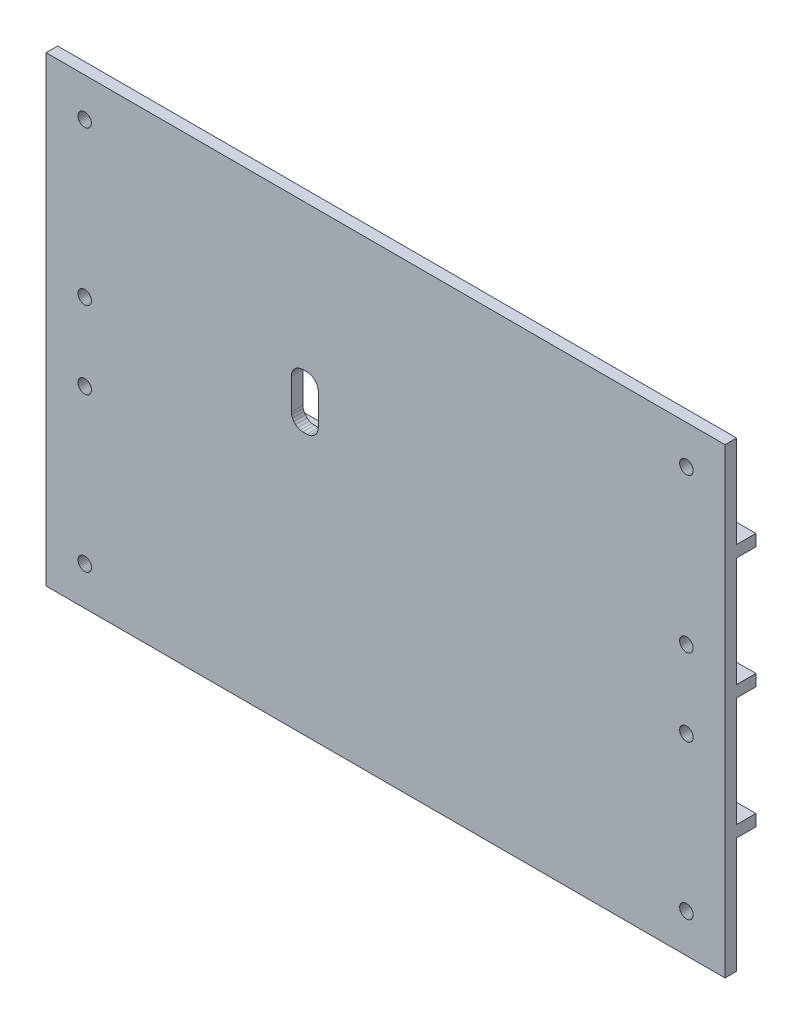
SolidWorks part; units mm, degrees
ref_plane "前视基准面" through (0, 0, 0) normal (0, 0, 1) x (1, 0, 0)
ref_plane "上视基准面" through (0, 0, 0) normal (0, 1, 0) x (1, 0, 0)
ref_plane "右视基准面" through (0, 0, 0) normal (1, 0, 0) x (0, 0, -1)
other "Configuration Table"
ref_plane "基准面1" through (0, 0, -5) normal (0, 0, -1) x (-1, 0, 0)
sketch "草图1" plane through (0, 0, -5) normal (0, 0, -1) x (-1, 0, 0)
  line L0 (-175.8, 0) -> (-175.8, -119.6)
  line L1 (-175.8, -119.6) -> (0, -119.6)
  line L2 (0, -119.6) -> (0, 0)
  line L3 (0, 0) -> (-175.8, 0)
extrude "凸台-拉伸1" add sketch "草图1" against normal blind 8
sketch "草图2" plane through (175.8, 0, 0) normal (1, 0, 0) x (0, 0, -1)
  line L0 (5, -119.6) -> (5, -89.7)
  line L1 (5, -89.7) -> (0, -89.7)
  line L2 (0, -89.7) -> (0, -119.6)
  line L3 (0, -119.6) -> (5, -119.6)
extrude "切除-拉伸1" cut sketch "草图2" against normal through all
sketch "草图3" plane through (175.8, 0, 0) normal (1, 0, 0) x (0, 0, -1)
  line L0 (0, 0) -> (0, -23.9)
  line L1 (0, -23.9) -> (5, -23.9)
  line L2 (5, -23.9) -> (5, 0)
  line L3 (5, 0) -> (0, 0)
extrude "切除-拉伸2" cut sketch "草图3" against normal through all
sketch "草图4" plane through (175.8, 0, 0) normal (1, 0, 0) x (0, 0, -1)
  line L0 (5, -55.3) -> (5, -26.9)
  line L1 (5, -26.9) -> (0, -26.9)
  line L2 (0, -26.9) -> (0, -55.3)
  line L3 (0, -55.3) -> (5, -55.3)
extrude "切除-拉伸3" cut sketch "草图4" against normal through all
sketch "草图5" plane through (175.8, 0, 0) normal (1, 0, 0) x (0, 0, -1)
  line L0 (5, -86.7) -> (5, -58.3)
  line L1 (5, -58.3) -> (0, -58.3)
  line L2 (0, -58.3) -> (0, -86.7)
  line L3 (0, -86.7) -> (5, -86.7)
extrude "切除-拉伸4" cut sketch "草图5" against normal through all
sketch "草图6" plane through (0, 0, 0) normal (0, 0, -1) x (-1, 0, 0)
  line L0 (-9.7257, -48.0716) -> (-10, -48.0506)
  line L1 (-10, -48.0506) -> (-10.2743, -48.0716)
  line L2 (-10.2743, -48.0716) -> (-10.54, -48.136)
  line L3 (-10.54, -48.136) -> (-10.7954, -48.2414)
  line L4 (-10.7954, -48.2414) -> (-11.0275, -48.3839)
  line L5 (-11.0275, -48.3839) -> (-11.238, -48.5636)
  line L6 (-11.238, -48.5636) -> (-11.4149, -48.7706)
  line L7 (-11.4149, -48.7706) -> (-11.5592, -49.0065)
  line L8 (-11.5592, -49.0065) -> (-11.6639, -49.2581)
  line L9 (-11.6639, -49.2581) -> (-11.7271, -49.5217)
  line L10 (-11.7271, -49.5217) -> (-11.75, -49.8)
  line L11 (-11.75, -49.8) -> (-11.7271, -50.0783)
  line L12 (-11.7271, -50.0783) -> (-11.6639, -50.3419)
  line L13 (-11.6639, -50.3419) -> (-11.5592, -50.5935)
  line L14 (-11.5592, -50.5935) -> (-11.4149, -50.8294)
  line L15 (-11.4149, -50.8294) -> (-11.238, -51.0364)
  line L16 (-11.238, -51.0364) -> (-11.0275, -51.2161)
  line L17 (-11.0275, -51.2161) -> (-10.7954, -51.3586)
  line L18 (-10.7954, -51.3586) -> (-10.54, -51.464)
  line L19 (-10.54, -51.464) -> (-10.2743, -51.5283)
  line L20 (-10.2743, -51.5283) -> (-10, -51.5494)
  line L21 (-10, -51.5494) -> (-9.7257, -51.5283)
  line L22 (-9.7257, -51.5283) -> (-9.46, -51.464)
  line L23 (-9.46, -51.464) -> (-9.2046, -51.3586)
  line L24 (-9.2046, -51.3586) -> (-8.9725, -51.2161)
  line L25 (-8.9725, -51.2161) -> (-8.762, -51.0364)
  line L26 (-8.762, -51.0364) -> (-8.5851, -50.8294)
  line L27 (-8.5851, -50.8294) -> (-8.4408, -50.5935)
  line L28 (-8.4408, -50.5935) -> (-8.3361, -50.3419)
  line L29 (-8.3361, -50.3419) -> (-8.2729, -50.0783)
  line L30 (-8.2729, -50.0783) -> (-8.25, -49.8)
  line L31 (-8.25, -49.8) -> (-8.2729, -49.5217)
  line L32 (-8.2729, -49.5217) -> (-8.3361, -49.2581)
  line L33 (-8.3361, -49.2581) -> (-8.4408, -49.0065)
  line L34 (-8.4408, -49.0065) -> (-8.5851, -48.7706)
  line L35 (-8.5851, -48.7706) -> (-8.762, -48.5636)
  line L36 (-8.762, -48.5636) -> (-8.9725, -48.3839)
  line L37 (-8.9725, -48.3839) -> (-9.2046, -48.2414)
  line L38 (-9.2046, -48.2414) -> (-9.46, -48.136)
  line L39 (-9.46, -48.136) -> (-9.7257, -48.0716)
extrude "切除-拉伸5" cut sketch "草图6" against normal through all
sketch "草图7" plane through (0, 0, 0) normal (0, 0, -1) x (-1, 0, 0)
  line L0 (-67.5, -37.8) -> (-68.1688, -37.8755)
  line L1 (-68.1688, -37.8755) -> (-68.8023, -38.0976)
  line L2 (-68.8023, -38.0976) -> (-69.3705, -38.4549)
  line L3 (-69.3705, -38.4549) -> (-69.8451, -38.9295)
  line L4 (-69.8451, -38.9295) -> (-70.2024, -39.4977)
  line L5 (-70.2024, -39.4977) -> (-70.4245, -40.1312)
  line L6 (-70.4245, -40.1312) -> (-70.5, -40.8)
  line L7 (-70.5, -40.8) -> (-70.5, -48.8)
  line L8 (-70.5, -48.8) -> (-70.4245, -49.4688)
  line L9 (-70.4245, -49.4688) -> (-70.2024, -50.1023)
  line L10 (-70.2024, -50.1023) -> (-69.8451, -50.6705)
  line L11 (-69.8451, -50.6705) -> (-69.3705, -51.1451)
  line L12 (-69.3705, -51.1451) -> (-68.8023, -51.5024)
  line L13 (-68.8023, -51.5024) -> (-68.1688, -51.7245)
  line L14 (-68.1688, -51.7245) -> (-67.5, -51.8)
  line L15 (-67.5, -51.8) -> (-66.5, -51.8)
  line L16 (-66.5, -51.8) -> (-65.8312, -51.7245)
  line L17 (-65.8312, -51.7245) -> (-65.1977, -51.5024)
  line L18 (-65.1977, -51.5024) -> (-64.6295, -51.1451)
  line L19 (-64.6295, -51.1451) -> (-64.1549, -50.6705)
  line L20 (-64.1549, -50.6705) -> (-63.7976, -50.1023)
  line L21 (-63.7976, -50.1023) -> (-63.5755, -49.4688)
  line L22 (-63.5755, -49.4688) -> (-63.5, -48.8)
  line L23 (-63.5, -48.8) -> (-63.5, -40.8)
  line L24 (-63.5, -40.8) -> (-63.5755, -40.1312)
  line L25 (-63.5755, -40.1312) -> (-63.7976, -39.4977)
  line L26 (-63.7976, -39.4977) -> (-64.1549, -38.9295)
  line L27 (-64.1549, -38.9295) -> (-64.6295, -38.4549)
  line L28 (-64.6295, -38.4549) -> (-65.1977, -38.0976)
  line L29 (-65.1977, -38.0976) -> (-65.8312, -37.8755)
  line L30 (-65.8312, -37.8755) -> (-66.5, -37.8)
  line L31 (-66.5, -37.8) -> (-67.5, -37.8)
extrude "切除-拉伸6" cut sketch "草图7" against normal through all
sketch "草图8" plane through (0, 0, 3) normal (0, 0, 1) x (1, 0, 0)
  line L0 (167.4639, -49.2581) -> (167.3592, -49.0065)
  line L1 (167.3592, -49.0065) -> (167.2149, -48.7706)
  line L2 (167.2149, -48.7706) -> (167.038, -48.5636)
  line L3 (167.038, -48.5636) -> (166.8275, -48.3839)
  line L4 (166.8275, -48.3839) -> (166.5954, -48.2414)
  line L5 (166.5954, -48.2414) -> (166.34, -48.136)
  line L6 (166.34, -48.136) -> (166.0743, -48.0716)
  line L7 (166.0743, -48.0716) -> (165.8, -48.0506)
  line L8 (165.8, -48.0506) -> (165.5257, -48.0716)
  line L9 (165.5257, -48.0716) -> (165.26, -48.136)
  line L10 (165.26, -48.136) -> (165.0046, -48.2414)
  line L11 (165.0046, -48.2414) -> (164.7725, -48.3839)
  line L12 (164.7725, -48.3839) -> (164.562, -48.5636)
  line L13 (164.562, -48.5636) -> (164.3851, -48.7706)
  line L14 (164.3851, -48.7706) -> (164.2408, -49.0065)
  line L15 (164.2408, -49.0065) -> (164.1361, -49.2581)
  line L16 (164.1361, -49.2581) -> (164.0729, -49.5217)
  line L17 (164.0729, -49.5217) -> (164.05, -49.8)
  line L18 (164.05, -49.8) -> (164.0729, -50.0783)
  line L19 (164.0729, -50.0783) -> (164.1361, -50.3419)
  line L20 (164.1361, -50.3419) -> (164.2408, -50.5935)
  line L21 (164.2408, -50.5935) -> (164.3851, -50.8294)
  line L22 (164.3851, -50.8294) -> (164.562, -51.0364)
  line L23 (164.562, -51.0364) -> (164.7725, -51.2161)
  line L24 (164.7725, -51.2161) -> (165.0046, -51.3586)
  line L25 (165.0046, -51.3586) -> (165.26, -51.464)
  line L26 (165.26, -51.464) -> (165.5257, -51.5283)
  line L27 (165.5257, -51.5283) -> (165.8, -51.5494)
  line L28 (165.8, -51.5494) -> (166.0743, -51.5283)
  line L29 (166.0743, -51.5283) -> (166.34, -51.464)
  line L30 (166.34, -51.464) -> (166.5954, -51.3586)
  line L31 (166.5954, -51.3586) -> (166.8275, -51.2161)
  line L32 (166.8275, -51.2161) -> (167.038, -51.0364)
  line L33 (167.038, -51.0364) -> (167.2149, -50.8294)
  line L34 (167.2149, -50.8294) -> (167.3592, -50.5935)
  line L35 (167.3592, -50.5935) -> (167.4639, -50.3419)
  line L36 (167.4639, -50.3419) -> (167.527, -50.0783)
  line L37 (167.527, -50.0783) -> (167.55, -49.8)
  line L38 (167.55, -49.8) -> (167.527, -49.5217)
  line L39 (167.527, -49.5217) -> (167.4639, -49.2581)
extrude "切除-拉伸7" cut sketch "草图8" against normal through all
sketch "草图9" plane through (0, 0, 0) normal (0, 0, -1) x (-1, 0, 0)
  line L0 (-8.25, -10) -> (-8.2729, -9.7217)
  line L1 (-8.2729, -9.7217) -> (-8.3361, -9.4581)
  line L2 (-8.3361, -9.4581) -> (-8.4408, -9.2065)
  line L3 (-8.4408, -9.2065) -> (-8.5851, -8.9706)
  line L4 (-8.5851, -8.9706) -> (-8.762, -8.7636)
  line L5 (-8.762, -8.7636) -> (-8.9725, -8.5839)
  line L6 (-8.9725, -8.5839) -> (-9.2046, -8.4414)
  line L7 (-9.2046, -8.4414) -> (-9.46, -8.336)
  line L8 (-9.46, -8.336) -> (-9.7257, -8.2716)
  line L9 (-9.7257, -8.2716) -> (-10, -8.2506)
  line L10 (-10, -8.2506) -> (-10.2743, -8.2716)
  line L11 (-10.2743, -8.2716) -> (-10.54, -8.336)
  line L12 (-10.54, -8.336) -> (-10.7954, -8.4414)
  line L13 (-10.7954, -8.4414) -> (-11.0275, -8.5839)
  line L14 (-11.0275, -8.5839) -> (-11.238, -8.7636)
  line L15 (-11.238, -8.7636) -> (-11.4149, -8.9706)
  line L16 (-11.4149, -8.9706) -> (-11.5592, -9.2065)
  line L17 (-11.5592, -9.2065) -> (-11.6639, -9.4581)
  line L18 (-11.6639, -9.4581) -> (-11.7271, -9.7217)
  line L19 (-11.7271, -9.7217) -> (-11.75, -10)
  line L20 (-11.75, -10) -> (-11.7271, -10.2783)
  line L21 (-11.7271, -10.2783) -> (-11.6639, -10.5419)
  line L22 (-11.6639, -10.5419) -> (-11.5592, -10.7935)
  line L23 (-11.5592, -10.7935) -> (-11.4149, -11.0294)
  line L24 (-11.4149, -11.0294) -> (-11.238, -11.2364)
  line L25 (-11.238, -11.2364) -> (-11.0275, -11.4161)
  line L26 (-11.0275, -11.4161) -> (-10.7954, -11.5586)
  line L27 (-10.7954, -11.5586) -> (-10.54, -11.664)
  line L28 (-10.54, -11.664) -> (-10.2743, -11.7284)
  line L29 (-10.2743, -11.7284) -> (-10, -11.7494)
  line L30 (-10, -11.7494) -> (-9.7257, -11.7284)
  line L31 (-9.7257, -11.7284) -> (-9.46, -11.664)
  line L32 (-9.46, -11.664) -> (-9.2046, -11.5586)
  line L33 (-9.2046, -11.5586) -> (-8.9725, -11.4161)
  line L34 (-8.9725, -11.4161) -> (-8.762, -11.2364)
  line L35 (-8.762, -11.2364) -> (-8.5851, -11.0294)
  line L36 (-8.5851, -11.0294) -> (-8.4408, -10.7935)
  line L37 (-8.4408, -10.7935) -> (-8.3361, -10.5419)
  line L38 (-8.3361, -10.5419) -> (-8.2729, -10.2783)
  line L39 (-8.2729, -10.2783) -> (-8.25, -10)
extrude "切除-拉伸8" cut sketch "草图9" against normal through all
sketch "草图10" plane through (0, 0, 3) normal (0, 0, 1) x (1, 0, 0)
  line L0 (166.0743, -8.2716) -> (165.8, -8.2506)
  line L1 (165.8, -8.2506) -> (165.5257, -8.2716)
  line L2 (165.5257, -8.2716) -> (165.26, -8.336)
  line L3 (165.26, -8.336) -> (165.0046, -8.4414)
  line L4 (165.0046, -8.4414) -> (164.7725, -8.5839)
  line L5 (164.7725, -8.5839) -> (164.562, -8.7636)
  line L6 (164.562, -8.7636) -> (164.3851, -8.9706)
  line L7 (164.3851, -8.9706) -> (164.2408, -9.2065)
  line L8 (164.2408, -9.2065) -> (164.1361, -9.4581)
  line L9 (164.1361, -9.4581) -> (164.0729, -9.7217)
  line L10 (164.0729, -9.7217) -> (164.05, -10)
  line L11 (164.05, -10) -> (164.0729, -10.2783)
  line L12 (164.0729, -10.2783) -> (164.1361, -10.5419)
  line L13 (164.1361, -10.5419) -> (164.2408, -10.7935)
  line L14 (164.2408, -10.7935) -> (164.3851, -11.0294)
  line L15 (164.3851, -11.0294) -> (164.562, -11.2364)
  line L16 (164.562, -11.2364) -> (164.7725, -11.4161)
  line L17 (164.7725, -11.4161) -> (165.0046, -11.5586)
  line L18 (165.0046, -11.5586) -> (165.26, -11.664)
  line L19 (165.26, -11.664) -> (165.5257, -11.7284)
  line L20 (165.5257, -11.7284) -> (165.8, -11.7494)
  line L21 (165.8, -11.7494) -> (166.0743, -11.7284)
  line L22 (166.0743, -11.7284) -> (166.34, -11.664)
  line L23 (166.34, -11.664) -> (166.5954, -11.5586)
  line L24 (166.5954, -11.5586) -> (166.8275, -11.4161)
  line L25 (166.8275, -11.4161) -> (167.038, -11.2364)
  line L26 (167.038, -11.2364) -> (167.2149, -11.0294)
  line L27 (167.2149, -11.0294) -> (167.3592, -10.7935)
  line L28 (167.3592, -10.7935) -> (167.4639, -10.5419)
  line L29 (167.4639, -10.5419) -> (167.527, -10.2783)
  line L30 (167.527, -10.2783) -> (167.55, -10)
  line L31 (167.55, -10) -> (167.527, -9.7217)
  line L32 (167.527, -9.7217) -> (167.4639, -9.4581)
  line L33 (167.4639, -9.4581) -> (167.3592, -9.2065)
  line L34 (167.3592, -9.2065) -> (167.2149, -8.9706)
  line L35 (167.2149, -8.9706) -> (167.038, -8.7636)
  line L36 (167.038, -8.7636) -> (166.8275, -8.5839)
  line L37 (166.8275, -8.5839) -> (166.5954, -8.4414)
  line L38 (166.5954, -8.4414) -> (166.34, -8.336)
  line L39 (166.34, -8.336) -> (166.0743, -8.2716)
extrude "切除-拉伸9" cut sketch "草图10" against normal through all
sketch "草图11" plane through (0, 0, 0) normal (0, 0, -1) x (-1, 0, 0)
  line L0 (-11.75, -69.8) -> (-11.7271, -70.0783)
  line L1 (-11.7271, -70.0783) -> (-11.6639, -70.3419)
  line L2 (-11.6639, -70.3419) -> (-11.5592, -70.5935)
  line L3 (-11.5592, -70.5935) -> (-11.4149, -70.8294)
  line L4 (-11.4149, -70.8294) -> (-11.238, -71.0364)
  line L5 (-11.238, -71.0364) -> (-11.0275, -71.2161)
  line L6 (-11.0275, -71.2161) -> (-10.7954, -71.3586)
  line L7 (-10.7954, -71.3586) -> (-10.54, -71.464)
  line L8 (-10.54, -71.464) -> (-10.2743, -71.5284)
  line L9 (-10.2743, -71.5284) -> (-10, -71.5494)
  line L10 (-10, -71.5494) -> (-9.7257, -71.5284)
  line L11 (-9.7257, -71.5284) -> (-9.46, -71.464)
  line L12 (-9.46, -71.464) -> (-9.2046, -71.3586)
  line L13 (-9.2046, -71.3586) -> (-8.9725, -71.2161)
  line L14 (-8.9725, -71.2161) -> (-8.762, -71.0364)
  line L15 (-8.762, -71.0364) -> (-8.5851, -70.8294)
  line L16 (-8.5851, -70.8294) -> (-8.4408, -70.5935)
  line L17 (-8.4408, -70.5935) -> (-8.3361, -70.3419)
  line L18 (-8.3361, -70.3419) -> (-8.2729, -70.0783)
  line L19 (-8.2729, -70.0783) -> (-8.25, -69.8)
  line L20 (-8.25, -69.8) -> (-8.2729, -69.5217)
  line L21 (-8.2729, -69.5217) -> (-8.3361, -69.2581)
  line L22 (-8.3361, -69.2581) -> (-8.4408, -69.0065)
  line L23 (-8.4408, -69.0065) -> (-8.5851, -68.7706)
  line L24 (-8.5851, -68.7706) -> (-8.762, -68.5636)
  line L25 (-8.762, -68.5636) -> (-8.9725, -68.3839)
  line L26 (-8.9725, -68.3839) -> (-9.2046, -68.2414)
  line L27 (-9.2046, -68.2414) -> (-9.46, -68.136)
  line L28 (-9.46, -68.136) -> (-9.7257, -68.0716)
  line L29 (-9.7257, -68.0716) -> (-10, -68.0506)
  line L30 (-10, -68.0506) -> (-10.2743, -68.0716)
  line L31 (-10.2743, -68.0716) -> (-10.54, -68.136)
  line L32 (-10.54, -68.136) -> (-10.7954, -68.2414)
  line L33 (-10.7954, -68.2414) -> (-11.0275, -68.3839)
  line L34 (-11.0275, -68.3839) -> (-11.238, -68.5636)
  line L35 (-11.238, -68.5636) -> (-11.4149, -68.7706)
  line L36 (-11.4149, -68.7706) -> (-11.5592, -69.0065)
  line L37 (-11.5592, -69.0065) -> (-11.6639, -69.2581)
  line L38 (-11.6639, -69.2581) -> (-11.7271, -69.5217)
  line L39 (-11.7271, -69.5217) -> (-11.75, -69.8)
extrude "切除-拉伸10" cut sketch "草图11" against normal through all
sketch "草图12" plane through (0, 0, 3) normal (0, 0, 1) x (1, 0, 0)
  line L0 (164.1361, -69.2581) -> (164.0729, -69.5217)
  line L1 (164.0729, -69.5217) -> (164.05, -69.8)
  line L2 (164.05, -69.8) -> (164.0729, -70.0783)
  line L3 (164.0729, -70.0783) -> (164.1361, -70.3419)
  line L4 (164.1361, -70.3419) -> (164.2408, -70.5935)
  line L5 (164.2408, -70.5935) -> (164.3851, -70.8294)
  line L6 (164.3851, -70.8294) -> (164.562, -71.0364)
  line L7 (164.562, -71.0364) -> (164.7725, -71.2161)
  line L8 (164.7725, -71.2161) -> (165.0046, -71.3586)
  line L9 (165.0046, -71.3586) -> (165.26, -71.464)
  line L10 (165.26, -71.464) -> (165.5257, -71.5284)
  line L11 (165.5257, -71.5284) -> (165.8, -71.5494)
  line L12 (165.8, -71.5494) -> (166.0743, -71.5284)
  line L13 (166.0743, -71.5284) -> (166.34, -71.464)
  line L14 (166.34, -71.464) -> (166.5954, -71.3586)
  line L15 (166.5954, -71.3586) -> (166.8275, -71.2161)
  line L16 (166.8275, -71.2161) -> (167.038, -71.0364)
  line L17 (167.038, -71.0364) -> (167.2149, -70.8294)
  line L18 (167.2149, -70.8294) -> (167.3592, -70.5935)
  line L19 (167.3592, -70.5935) -> (167.4639, -70.3419)
  line L20 (167.4639, -70.3419) -> (167.527, -70.0783)
  line L21 (167.527, -70.0783) -> (167.55, -69.8)
  line L22 (167.55, -69.8) -> (167.527, -69.5217)
  line L23 (167.527, -69.5217) -> (167.4639, -69.2581)
  line L24 (167.4639, -69.2581) -> (167.3592, -69.0065)
  line L25 (167.3592, -69.0065) -> (167.2149, -68.7706)
  line L26 (167.2149, -68.7706) -> (167.038, -68.5636)
  line L27 (167.038, -68.5636) -> (166.8275, -68.3839)
  line L28 (166.8275, -68.3839) -> (166.5954, -68.2414)
  line L29 (166.5954, -68.2414) -> (166.34, -68.136)
  line L30 (166.34, -68.136) -> (166.0743, -68.0716)
  line L31 (166.0743, -68.0716) -> (165.8, -68.0506)
  line L32 (165.8, -68.0506) -> (165.5257, -68.0716)
  line L33 (165.5257, -68.0716) -> (165.26, -68.136)
  line L34 (165.26, -68.136) -> (165.0046, -68.2414)
  line L35 (165.0046, -68.2414) -> (164.7725, -68.3839)
  line L36 (164.7725, -68.3839) -> (164.562, -68.5636)
  line L37 (164.562, -68.5636) -> (164.3851, -68.7706)
  line L38 (164.3851, -68.7706) -> (164.2408, -69.0065)
  line L39 (164.2408, -69.0065) -> (164.1361, -69.2581)
extrude "切除-拉伸11" cut sketch "草图12" against normal through all
sketch "草图13" plane through (0, 0, 0) normal (0, 0, -1) x (-1, 0, 0)
  line L0 (-9.7257, -107.8717) -> (-10, -107.8506)
  line L1 (-10, -107.8506) -> (-10.2743, -107.8717)
  line L2 (-10.2743, -107.8717) -> (-10.54, -107.936)
  line L3 (-10.54, -107.936) -> (-10.7954, -108.0414)
  line L4 (-10.7954, -108.0414) -> (-11.0275, -108.1839)
  line L5 (-11.0275, -108.1839) -> (-11.238, -108.3636)
  line L6 (-11.238, -108.3636) -> (-11.4149, -108.5705)
  line L7 (-11.4149, -108.5705) -> (-11.5592, -108.8065)
  line L8 (-11.5592, -108.8065) -> (-11.6639, -109.0581)
  line L9 (-11.6639, -109.0581) -> (-11.7271, -109.3217)
  line L10 (-11.7271, -109.3217) -> (-11.75, -109.6)
  line L11 (-11.75, -109.6) -> (-11.7271, -109.8783)
  line L12 (-11.7271, -109.8783) -> (-11.6639, -110.1419)
  line L13 (-11.6639, -110.1419) -> (-11.5592, -110.3935)
  line L14 (-11.5592, -110.3935) -> (-11.4149, -110.6294)
  line L15 (-11.4149, -110.6294) -> (-11.238, -110.8364)
  line L16 (-11.238, -110.8364) -> (-11.0275, -111.016)
  line L17 (-11.0275, -111.016) -> (-10.7954, -111.1586)
  line L18 (-10.7954, -111.1586) -> (-10.54, -111.264)
  line L19 (-10.54, -111.264) -> (-10.2743, -111.3284)
  line L20 (-10.2743, -111.3284) -> (-10, -111.3494)
  line L21 (-10, -111.3494) -> (-9.7257, -111.3284)
  line L22 (-9.7257, -111.3284) -> (-9.46, -111.264)
  line L23 (-9.46, -111.264) -> (-9.2046, -111.1586)
  line L24 (-9.2046, -111.1586) -> (-8.9725, -111.016)
  line L25 (-8.9725, -111.016) -> (-8.762, -110.8364)
  line L26 (-8.762, -110.8364) -> (-8.5851, -110.6294)
  line L27 (-8.5851, -110.6294) -> (-8.4408, -110.3935)
  line L28 (-8.4408, -110.3935) -> (-8.3361, -110.1419)
  line L29 (-8.3361, -110.1419) -> (-8.2729, -109.8783)
  line L30 (-8.2729, -109.8783) -> (-8.25, -109.6)
  line L31 (-8.25, -109.6) -> (-8.2729, -109.3217)
  line L32 (-8.2729, -109.3217) -> (-8.3361, -109.0581)
  line L33 (-8.3361, -109.0581) -> (-8.4408, -108.8065)
  line L34 (-8.4408, -108.8065) -> (-8.5851, -108.5705)
  line L35 (-8.5851, -108.5705) -> (-8.762, -108.3636)
  line L36 (-8.762, -108.3636) -> (-8.9725, -108.1839)
  line L37 (-8.9725, -108.1839) -> (-9.2046, -108.0414)
  line L38 (-9.2046, -108.0414) -> (-9.46, -107.936)
  line L39 (-9.46, -107.936) -> (-9.7257, -107.8717)
extrude "切除-拉伸12" cut sketch "草图13" against normal through all
sketch "草图14" plane through (0, 0, 0) normal (0, 0, -1) x (-1, 0, 0)
  line L0 (-165.8, -111.3494) -> (-165.5257, -111.3284)
  line L1 (-165.5257, -111.3284) -> (-165.26, -111.264)
  line L2 (-165.26, -111.264) -> (-165.0046, -111.1586)
  line L3 (-165.0046, -111.1586) -> (-164.7725, -111.016)
  line L4 (-164.7725, -111.016) -> (-164.562, -110.8364)
  line L5 (-164.562, -110.8364) -> (-164.3851, -110.6294)
  line L6 (-164.3851, -110.6294) -> (-164.2408, -110.3935)
  line L7 (-164.2408, -110.3935) -> (-164.1361, -110.1419)
  line L8 (-164.1361, -110.1419) -> (-164.0729, -109.8783)
  line L9 (-164.0729, -109.8783) -> (-164.05, -109.6)
  line L10 (-164.05, -109.6) -> (-164.0729, -109.3217)
  line L11 (-164.0729, -109.3217) -> (-164.1361, -109.0581)
  line L12 (-164.1361, -109.0581) -> (-164.2408, -108.8065)
  line L13 (-164.2408, -108.8065) -> (-164.3851, -108.5705)
  line L14 (-164.3851, -108.5705) -> (-164.562, -108.3636)
  line L15 (-164.562, -108.3636) -> (-164.7725, -108.1839)
  line L16 (-164.7725, -108.1839) -> (-165.0046, -108.0414)
  line L17 (-165.0046, -108.0414) -> (-165.26, -107.936)
  line L18 (-165.26, -107.936) -> (-165.5257, -107.8717)
  line L19 (-165.5257, -107.8717) -> (-165.8, -107.8506)
  line L20 (-165.8, -107.8506) -> (-166.0743, -107.8717)
  line L21 (-166.0743, -107.8717) -> (-166.34, -107.936)
  line L22 (-166.34, -107.936) -> (-166.5954, -108.0414)
  line L23 (-166.5954, -108.0414) -> (-166.8275, -108.1839)
  line L24 (-166.8275, -108.1839) -> (-167.038, -108.3636)
  line L25 (-167.038, -108.3636) -> (-167.2149, -108.5705)
  line L26 (-167.2149, -108.5705) -> (-167.3592, -108.8065)
  line L27 (-167.3592, -108.8065) -> (-167.4639, -109.0581)
  line L28 (-167.4639, -109.0581) -> (-167.527, -109.3217)
  line L29 (-167.527, -109.3217) -> (-167.55, -109.6)
  line L30 (-167.55, -109.6) -> (-167.527, -109.8783)
  line L31 (-167.527, -109.8783) -> (-167.4639, -110.1419)
  line L32 (-167.4639, -110.1419) -> (-167.3592, -110.3935)
  line L33 (-167.3592, -110.3935) -> (-167.2149, -110.6294)
  line L34 (-167.2149, -110.6294) -> (-167.038, -110.8364)
  line L35 (-167.038, -110.8364) -> (-166.8275, -111.016)
  line L36 (-166.8275, -111.016) -> (-166.5954, -111.1586)
  line L37 (-166.5954, -111.1586) -> (-166.34, -111.264)
  line L38 (-166.34, -111.264) -> (-166.0743, -111.3284)
  line L39 (-166.0743, -111.3284) -> (-165.8, -111.3494)
extrude "切除-拉伸13" cut sketch "草图14" against normal through all
